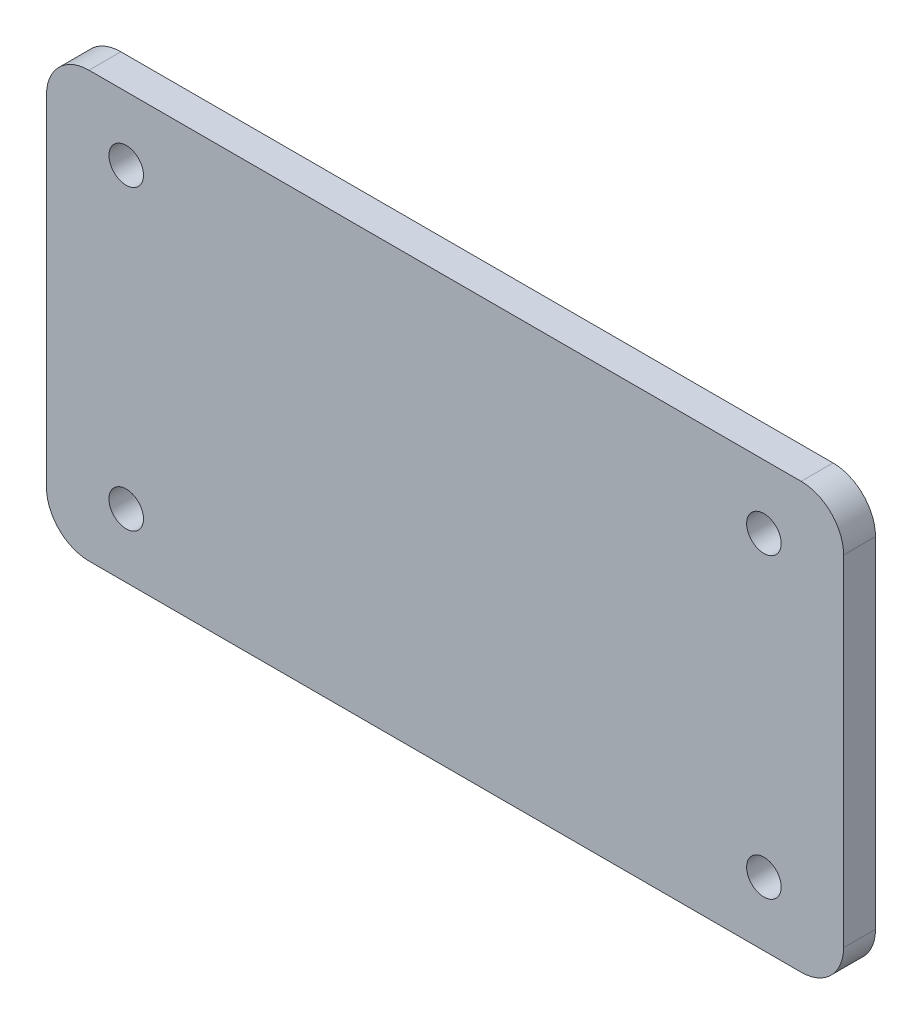
SolidWorks part; units mm, degrees
material "6063-T6"
ref_plane "Front Plane" through (0, 0, 0) normal (0, 0, 1) x (1, 0, 0)
ref_plane "Top Plane" through (0, 0, 0) normal (0, 1, 0) x (1, 0, 0)
ref_plane "Right Plane" through (0, 0, 0) normal (1, 0, 0) x (0, 0, -1)
sketch "Sketch2" plane through (0, 0, 0) normal (0, 0, 1) x (1, 0, 0)
  line L1 (-75, -40) -> (75, -40)
  line L2 (-75, -40) -> (-75, 40)
  line L3 (-75, 40) -> (75, 40)
  line L4 (75, -40) -> (75, 40)
  line L5 (-75, -40) -> (75, 40) construction
  line L6 (-75, 40) -> (75, -40) construction
  point P0 (0, 0)
  dimension "D1" = 150
  dimension "D2" = 80
extrude "Boss-Extrude1" add sketch "Sketch2" along normal mid plane 6
sketch "Sketch3" plane through (0, 0, 3) normal (0, 0, 1) x (1, 0, 0)
  line L4 (75, -40) -> (75, 40)
  line L5 (75, 40) -> (-75, 40)
  line L6 (-75, 40) -> (-75, -40)
  line L7 (-75, -40) -> (75, -40)
  line L8 (75, -40) -> (75, 40)
  line L9 (75, 40) -> (-75, 40)
  line L10 (-75, 40) -> (-75, -40)
  line L11 (-75, -40) -> (75, -40)
  circle A0 centre (-60, 28) radius 3.25
  circle A1 centre (-60, -28) radius 3.25
  circle A2 centre (60, -28) radius 3.25
  circle A3 centre (60, 28) radius 3.25
  dimension "D3" = 6.5
  dimension "D4" = 15
  dimension "D5" = 12
  dimension "D6" = 12
  dimension "D7" = 15
  dimension "D8" = 15
  dimension "D9" = 12
  dimension "D10" = 15
  dimension "D11" = 12
  dimension "D1" = 0
extrude "Cut-Extrude1" cut sketch "Sketch3" against normal through all both and the other way through all
fillet "Fillet2" radius 8 4 edges at (75, 40, 0) (75, -40, 0) (-75, -40, 0) (-75, 40, 0)
